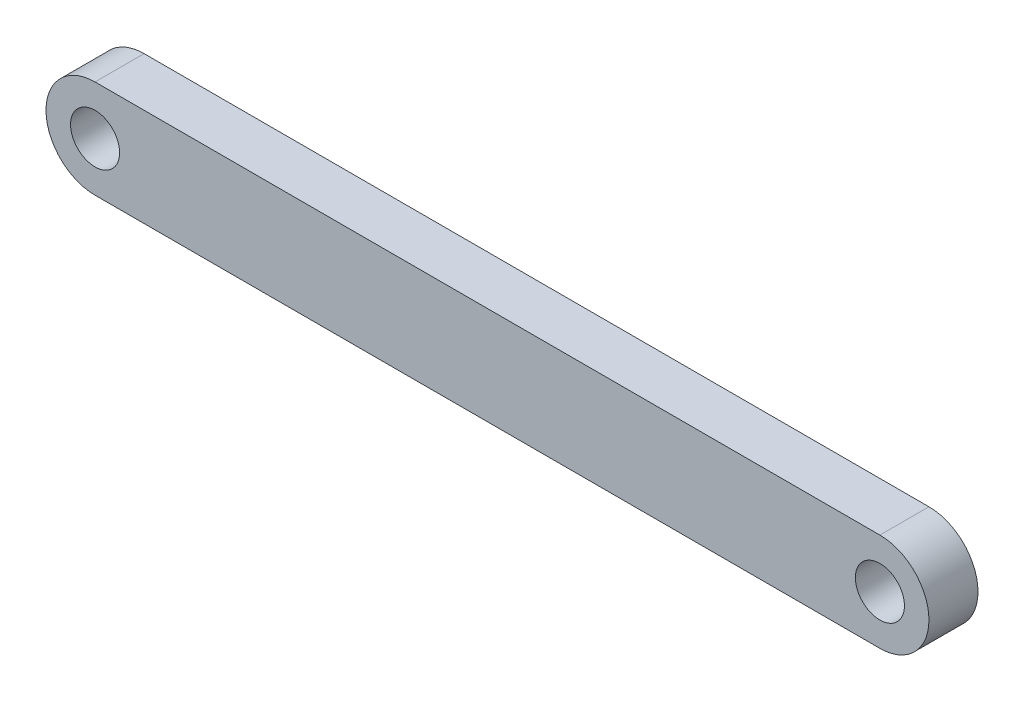
SolidWorks part; units mm, degrees
ref_plane "Front Plane" through (0, 0, 0) normal (0, 0, 1) x (1, 0, 0)
ref_plane "Top Plane" through (0, 0, 0) normal (0, 1, 0) x (1, 0, 0)
ref_plane "Right Plane" through (0, 0, 0) normal (1, 0, 0) x (0, 0, -1)
sketch "Sketch2" plane through (0, 0, 0) normal (0, 0, 1) x (1, 0, 0)
  line L0 (-47.9645, 0) -> (32.0355, 0) construction
  line L1 (-47.9645, 5) -> (32.0355, 5)
  line L2 (-47.9645, -5) -> (32.0355, -5)
  arc A0 (-47.9645, 5) -> (-47.9645, -5) centre (-47.9645, 0) ccw
  arc A1 (32.0355, -5) -> (32.0355, 5) centre (32.0355, 0) ccw
  circle A2 centre (-47.9645, 0) radius 2.5
  circle A3 centre (32.0355, 0) radius 2.5
  point P3 (-7.9645, 0)
extrude "Boss-Extrude1" add sketch "Sketch2" along normal blind 5
